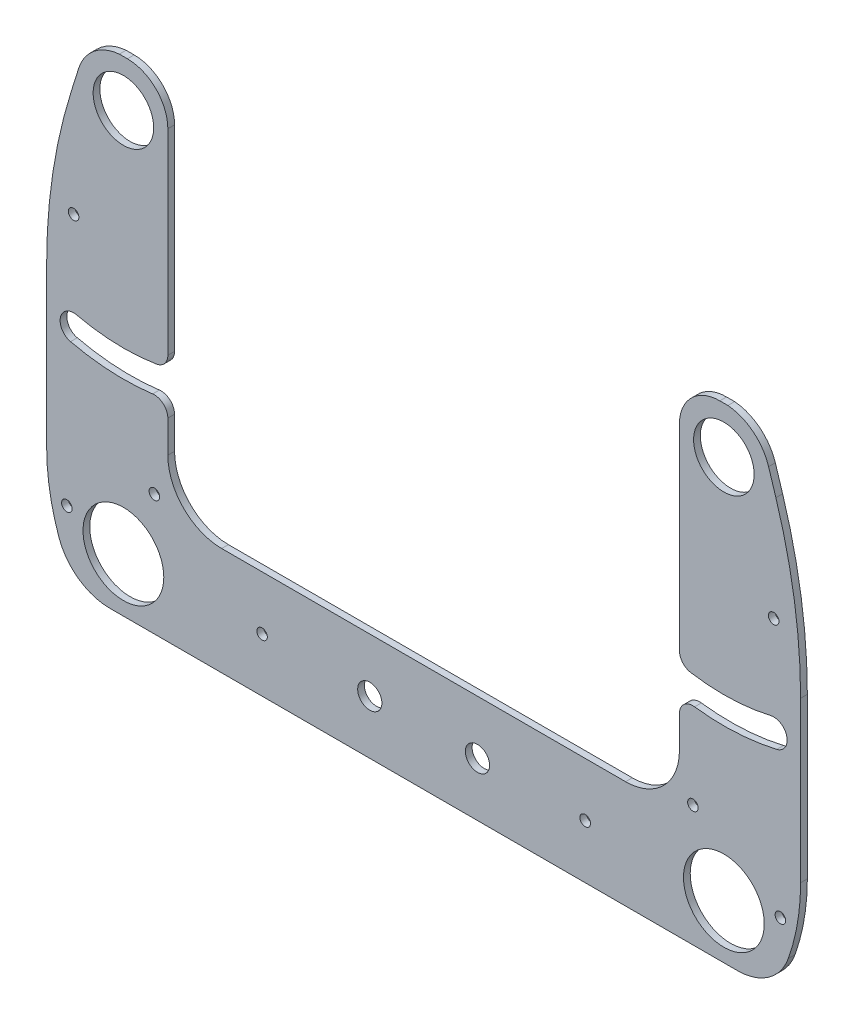
SolidWorks part; units mm, degrees
material "6061 Alloy"
ref_plane "Front Plane" through (0, 0, 0) normal (0, 0, 1) x (1, 0, 0)
ref_plane "Top Plane" through (0, 0, 0) normal (0, 1, 0) x (1, 0, 0)
ref_plane "Right Plane" through (0, 0, 0) normal (1, 0, 0) x (0, 0, -1)
sketch "Sketch1" plane through (0, 0, 0) normal (0, 0, 1) x (1, 0, 0)
  line L5 (120.65, -152.4) -> (120.65, -6.35)
  line L6 (127, 0) -> (171.45, 0) construction
  line L7 (177.8, -6.35) -> (177.8, -222.25)
  line L10 (0, -206.2199) -> (0, -63.6275) construction
  line L11 (-54.9244, 0) -> (300.6756, 0) construction
  line L13 (12.7, -177.8) -> (95.25, -177.8)
  line L14 (12.7, -228.6) -> (171.45, -228.6)
  line L15 (141.605, -22.0269) -> (141.605, -80.9091) construction
  line L16 (141.605, -22.0269) -> (141.605, -123.6269) construction
  line L19 (-141.605, -19.05) -> (-141.605, -77.9322) construction
  line L20 (141.605, -22.0269) -> (141.605, -203.2) construction
  line L22 (-120.65, -152.4) -> (-120.65, -6.35)
  line L23 (-12.7, -177.8) -> (-95.25, -177.8)
  line L24 (-12.7, -228.6) -> (-171.45, -228.6)
  line L25 (-177.8, -6.35) -> (-177.8, -222.25)
  line L26 (-12.7, -177.8) -> (12.7, -177.8)
  line L27 (-12.7, -228.6) -> (12.7, -228.6)
  line L28 (-177.8, -6.35) -> (-177.8, 6.35)
  line L29 (-165.1, 19.05) -> (-133.35, 19.05)
  line L30 (-120.65, 6.35) -> (-120.65, -6.35)
  line L31 (120.65, 6.35) -> (120.65, -6.35)
  line L32 (177.8, -6.35) -> (177.8, 6.35)
  line L33 (165.1, 19.05) -> (133.35, 19.05)
  arc A0 (95.25, -177.8) -> (120.65, -152.4) centre (95.25, -152.4) ccw
  arc A4 (120.65, -6.35) -> (127, 0) centre (127, -6.35) cw construction
  circle A8 centre (141.605, -22.0269) radius 14.2875
  circle A9 centre (141.605, -22.0269) radius 38.1 construction
  arc A10 (177.8, -6.35) -> (171.45, 0) centre (171.45, -6.35) ccw construction
  arc A11 (171.45, -228.6) -> (177.8, -222.25) centre (171.45, -222.25) ccw
  arc A14 (141.605, -79.1769) -> (120.9214, -75.3027) centre (141.605, -22.0269) ccw construction
  arc A15 (-141.605, -79.1769) -> (-120.9214, -75.3027) centre (-141.605, -22.0269) cw construction
  circle A16 centre (-141.605, -22.0269) radius 38.1 construction
  circle A17 centre (-141.605, -22.0269) radius 14.2875
  arc A19 (-95.25, -177.8) -> (-120.65, -152.4) centre (-95.25, -152.4) cw
  circle A20 centre (141.605, -123.6269) radius 38.1 construction
  circle A21 centre (-141.605, -123.6269) radius 38.1 construction
  arc A23 (-171.45, -228.6) -> (-177.8, -222.25) centre (-171.45, -222.25) cw
  circle A24 centre (-141.605, -203.2) radius 19.05
  circle A37 centre (141.605, -203.2) radius 19.05
  circle A39 centre (-76.2, -203.2) radius 2.4892
  circle A40 centre (76.2, -203.2) radius 2.4892
  circle A42 centre (-25.4, -203.2) radius 5.715
  arc A44 (-133.35, 19.05) -> (-120.65, 6.35) centre (-133.35, 6.35) cw
  arc A45 (-177.8, 6.35) -> (-165.1, 19.05) centre (-165.1, 6.35) cw
  arc A46 (133.35, 19.05) -> (120.65, 6.35) centre (133.35, 6.35) ccw
  arc A47 (177.8, 6.35) -> (165.1, 19.05) centre (165.1, 6.35) ccw
  circle A50 centre (-149.225, 6.35) radius 2.4892
  circle A53 centre (149.225, 6.35) radius 2.4892
  circle A54 centre (-168.275, -196.85) radius 2.4892
  circle A56 centre (168.275, -196.85) radius 2.4892
  circle A58 centre (-165.1, -76.2) radius 2.4892
  circle A59 centre (165.1, -76.2) radius 2.4892
  circle A60 centre (-127, -171.45) radius 2.4892
  circle A61 centre (127, -171.45) radius 2.4892
  circle A62 centre (25.4, -203.2) radius 5.715
  point P2 (177.8, -44.45)
  point P18 (177.8, 0)
  point P23 (177.8, -228.6)
  point P24 (177.8, -228.6)
  point P31 (177.8, 0)
  point P48 (-177.8, 0)
  point P49 (-177.8, -228.6)
  point P51 (-177.8, -44.45)
  point P78 (-141.605, -203.2)
  dimension "D6" = 25.4
  dimension "D7" = 6.35
  dimension "D8" = 6.35
  dimension "D9" = 177.8
  dimension "D10" = 28.575
  dimension "D12" = 76.2
  dimension "D13" = 57.15
  dimension "D15" = 38.1
  dimension "D18" = 76.2
  dimension "D21" = 4.9784
  dimension "D29" = 9.525
  dimension "D32" = 4.9784
  dimension "D35" = 11.43
  dimension "D40" = 12.7
  dimension "D43" = 4.9784
  dimension "D45" = 12.7
  dimension "D30" = 4.9784
  dimension "D41" = 4.9784
  dimension "D22" = 6.35
  dimension "D2" = 120.65
  dimension "D3" = 177.8
  dimension "D4" = 228.6
  dimension "D5" = 177.8
  dimension "D11" = 20.955
  dimension "`" = 22.0269
  dimension "D14" = 57.15
  dimension "D16" = 184.15
  dimension "D17" = 101.6
  dimension "D19" = 25.4
  dimension "D20" = 101.6
  dimension "D23" = 57.15
  dimension "D25" = 25.4
  dimension "D26" = 31.75
  dimension "D27" = 25.4
  dimension "D28" = 25.4
  dimension "D31" = 25.4
  dimension "D33" = 12.7
  dimension "D34" = 25.4
  dimension "D39" = 19.05
  dimension "D44" = 28.575
  dimension "D24" = 95.25
extrude "Boss-Extrude3" add sketch "Sketch1" along normal blind 3.175
sketch "Sketch2" plane through (0, 0, 3.175) normal (0, 0, 1) x (1, 0, 0)
  line L0 (177.8, -222.25) -> (177.8, 6.35) construction
  line L1 (-177.8, 19.05) -> (177.8, 19.05)
  line L2 (-177.8, 19.05) -> (-177.8, 0)
  line L3 (-177.8, 0) -> (177.8, 0)
  line L4 (177.8, 19.05) -> (177.8, 0)
  line L5 (-177.8, 6.35) -> (-177.8, -222.25) construction
  line L7 (-133.35, 19.05) -> (-165.1, 19.05) construction
  dimension "D1" = 19.05
extrude "Cut-Extrude1" cut sketch "Sketch2" against normal through all
fillet "Fillet1" radius 19.05 4 edges at (177.8, 0, 1.5875) (120.65, 0, 1.5875) (-120.65, 0, 1.5875) (-177.8, 0, 1.5875)
sketch "Sketch3" plane through (0, 0, 3.175) normal (0, 0, 1) x (1, 0, 0)
  line L2 (-177.8, -19.05) -> (-177.8, -222.25) construction
  line L3 (-158.75, 0) -> (-139.7, 0) construction
  line L4 (-177.8, -63.5) -> (-177.8, 0)
  line L5 (-177.8, 0) -> (-139.7, 0)
  line L6 (-177.8, -63.5) -> (-162.6988, -15.4039)
  arc A3 (-139.7, 0) -> (-162.6988, -15.4039) centre (-141.605, -22.0269) ccw
  dimension "D1" = 63.5
extrude "Cut-Extrude2" cut sketch "Sketch3" against normal through all
ref_plane "Plane1" through (0, 0, 0) normal (-1, 0, 0) x (0, 0, 1)
mirror "Mirror1" about plane through (0, 0, 0) normal (-1, 0, 0) of "Cut-Extrude2"
fillet "Fillet2" radius 254 2 edges at (177.8, -63.5, 1.5875) (-177.8, -63.5, 1.5875)
sketch "Sketch4" plane through (0, 0, 3.175) normal (0, 0, 1) x (1, 0, 0)
  line L0 (0, -177.8) -> (0, -13.685) construction
  line L5 (-177.8, -102.4383) -> (-177.8, -222.25) construction
  line L6 (-171.45, -228.6) -> (171.45, -228.6) construction
  line L7 (-177.8, -177.8) -> (-177.8, -228.6)
  line L8 (-177.8, -228.6) -> (-164.1882, -228.6)
  line L9 (177.8, -177.8) -> (177.8, -228.6)
  line L10 (177.8, -228.6) -> (164.1882, -228.6)
  circle A0 centre (-76.2, -177.8) radius 101.6 construction
  arc A1 (-177.8, -177.8) -> (-164.1882, -228.6) centre (-76.2, -177.8) ccw
  arc A2 (177.8, -177.8) -> (164.1882, -228.6) centre (76.2, -177.8) cw
  dimension "D1" = 203.2
  dimension "D2" = 50.8
extrude "Cut-Extrude3" cut sketch "Sketch4" against normal through all contours L8 A1 L7 | L9 L10 A2
fillet "Fillet3" radius 25.4 2 edges at (164.1882, -228.6, 1.5875) (-164.1882, -228.6, 1.5875)
sketch "Sketch5" plane through (0, 0, 3.175) normal (0, 0, 1) x (1, 0, 0)
  line L2 (-120.65, -129.7962) -> (-120.65, -116.8262)
  line L5 (120.65, -129.7962) -> (120.65, -116.8262)
  line L6 (120.65, -19.05) -> (120.65, -152.4) construction
  line L7 (177.8, -177.8) -> (177.8, -102.4383) construction
  line L8 (0, -203.7675) -> (0, -15.567) construction
  circle A4 centre (141.605, -22.0269) radius 103.4377 construction
  arc A5 (120.65, -116.8262) -> (163.6577, -116.5769) centre (141.605, -22.0269) ccw
  arc A6 (120.65, -129.7962) -> (166.5423, -128.9449) centre (141.605, -22.0269) ccw
  arc A9 (166.5423, -128.9449) -> (163.6577, -116.5769) centre (165.1, -122.7609) ccw
  arc A10 (-120.65, -129.7962) -> (-166.5423, -128.9449) centre (-141.605, -22.0269) cw
  arc A11 (-120.65, -116.8262) -> (-163.6577, -116.5769) centre (-141.605, -22.0269) cw
  arc A12 (-166.5423, -128.9449) -> (-163.6577, -116.5769) centre (-165.1, -122.7609) cw
  dimension "D1" = 97.0877
  dimension "D2" = 109.7877
  dimension "D4" = 12.7
  dimension "D3" = 206.8754
extrude "Cut-Extrude4" cut sketch "Sketch5" against normal through all contours A10 A12 A11 L2 | A9 A5 L5 A6
fillet "Fillet4" radius 6.35 4 edges at (120.65, -129.7962, 1.5875) (120.65, -116.8262, 1.5875) (-120.65, -129.7962, 1.5875) (-120.65, -116.8262, 1.5875)
sketch "Sketch6" plane through (0, 0, 0) normal (0, 0, -1) x (-1, 0, 0)
  line L1 (-743.0643, -231.14) -> (49256.9357, -231.14) construction
  line L2 (-180.34, -1269.6837) -> (-180.34, 48730.3163) construction
  line L3 (148.042, -228.6) -> (-148.042, -228.6) construction
  circle A0 centre (-76.2, -203.2) radius 2.4892 construction
  point P11 (-180.34, -231.14)
  point P13 (0, 0)
  point P16 (0, 0)
  dimension "D3" = 104.14
  dimension "D1" = 2.54
